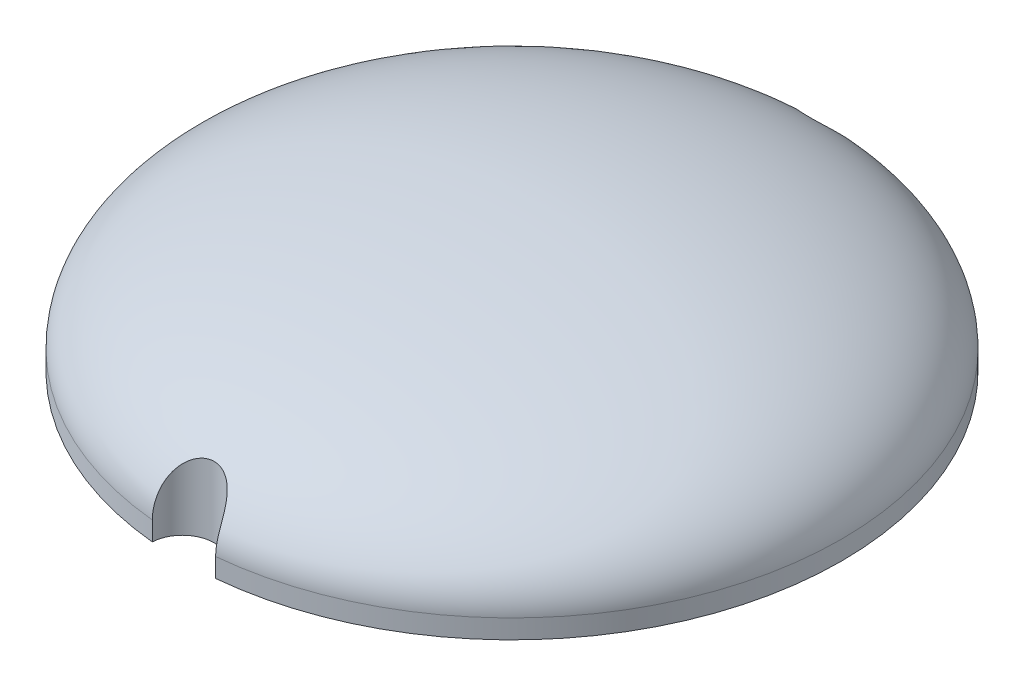
SolidWorks part; units mm, degrees
ref_plane "Front Plane" through (0, 0, 0) normal (0, 0, 1) x (1, 0, 0)
ref_plane "Top Plane" through (0, 0, 0) normal (0, 1, 0) x (1, 0, 0)
ref_plane "Right Plane" through (0, 0, 0) normal (1, 0, 0) x (0, 0, -1)
sketch "Sketch89" plane through (0, 0, 0) normal (0, 1, 0) x (1, 0, 0)
  circle A2 centre (0, 0) radius 24
  circle A5 centre (0, 0) radius 26
  dimension "D2" = 48
  dimension "D1" = 2
extrude "Boss-Extrude1" add sketch "Sketch89" along normal blind 1.5
sketch "Sketch91" plane through (0, 0, 3.7425) normal (1, 0, 0) x (0, 0, -1)
  line L0 (3.7425, 14.2649) -> (3.7425, -23.309) construction
sketch "Sketch92" plane through (0, 0, 2.8783) normal (-1, 0, 0) x (0, 0, 1)
  line L0 (-2.8783, 1.5) -> (21.1217, 1.5) construction
  line L1 (-2.8783, 9.5) -> (-2.8783, 1.5) construction
  line L3 (-2.8783, 9.5) -> (-2.8783, 11)
  line L4 (23.1217, 1.5) -> (21.1217, 1.5)
  line L11 (-2.8783, 200014.2649) -> (-2.8783, -200023.309) construction
  ellipse E0 centre (-2.8783, 1.5) end of major axis (-26.8783, 1.5) minor radius 8 (-2.8783, 9.5) -> (21.1217, 1.5) cw
  ellipse E1 centre (-2.8783, 1.5) end of major axis (-28.8783, 1.5) minor radius 9.5 (-2.8783, 11) -> (23.1217, 1.5) cw
  dimension "D1" = 8
  dimension "D2" = 1.5
revolve "Revolve1" add sketch "Sketch92" angle 360 about L0
sketch "Sketch93" plane through (0, 0, 0) normal (0, 1, 0) x (1, 0, 0)
  line L0 (0, 26) -> (0, -26) construction
  circle A0 centre (0, 26) radius 2.5
  circle A1 centre (0, 0) radius 26 construction
  circle A2 centre (0, -26) radius 2.5
  dimension "D1" = 5
sketch "Sketch94" plane through (0, 0, 0) normal (0, 1, 0) x (1, 0, 0)
  arc A0 (-3.9881, 25.6923) -> (3.9881, 25.6923) centre (0, 26) ccw
  circle A1 centre (0, 0) radius 26 construction
  arc A2 (3.9881, -25.6923) -> (-3.9881, -25.6923) centre (0, -26) ccw
  arc A3 (-3.9881, 25.6923) -> (3.9881, 25.6923) centre (0, 0) cw
  arc A4 (3.9881, -25.6923) -> (-3.9881, -25.6923) centre (0, 0) cw
  dimension "D1" = 4
extrude "Boss-Extrude2" add sketch "Sketch94" along normal up to surface (1.5 mm away)
extrude "Cut-Extrude6" cut sketch "Sketch93" along normal through all
